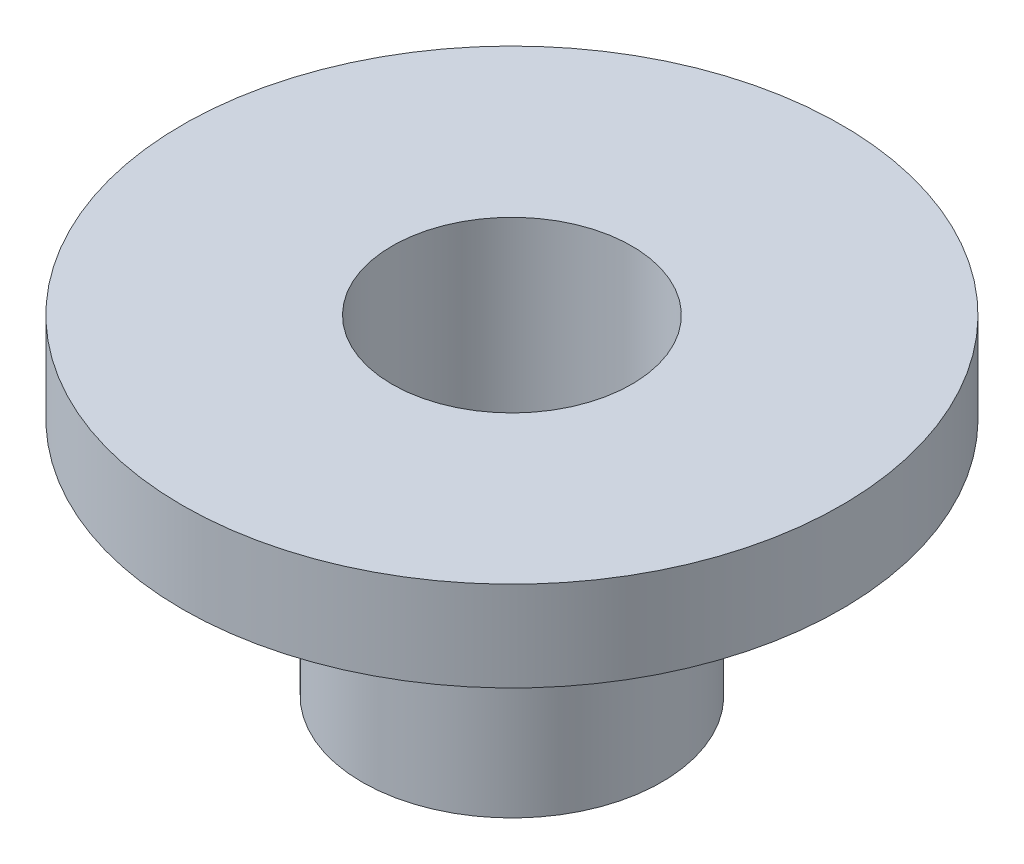
SolidWorks part; units mm, degrees
ref_plane "Přední rovina" through (0, 0, 0) normal (0, 0, 1) x (1, 0, 0)
ref_plane "Horní rovina" through (0, 0, 0) normal (0, 1, 0) x (1, 0, 0)
ref_plane "Pravá rovina" through (0, 0, 0) normal (1, 0, 0) x (0, 0, -1)
sketch "Skica1" plane through (0, 0, 0) normal (0, 1, 0) x (1, 0, 0)
  circle A0 centre (0, 0) radius 4
  circle A1 centre (0, 0) radius 5
  dimension "D1" = 8
  dimension "D2" = 10
extrude "Přidat vysunutím1" add sketch "Skica1" along normal blind 8
sketch "Skica2" plane through (0, 8, 0) normal (0, 1, 0) x (1, 0, 0)
  circle A0 centre (0, 0) radius 4
  circle A1 centre (0, 0) radius 11
  dimension "D1" = 22
extrude "Přidat vysunutím2" add sketch "Skica2" along normal blind 3
